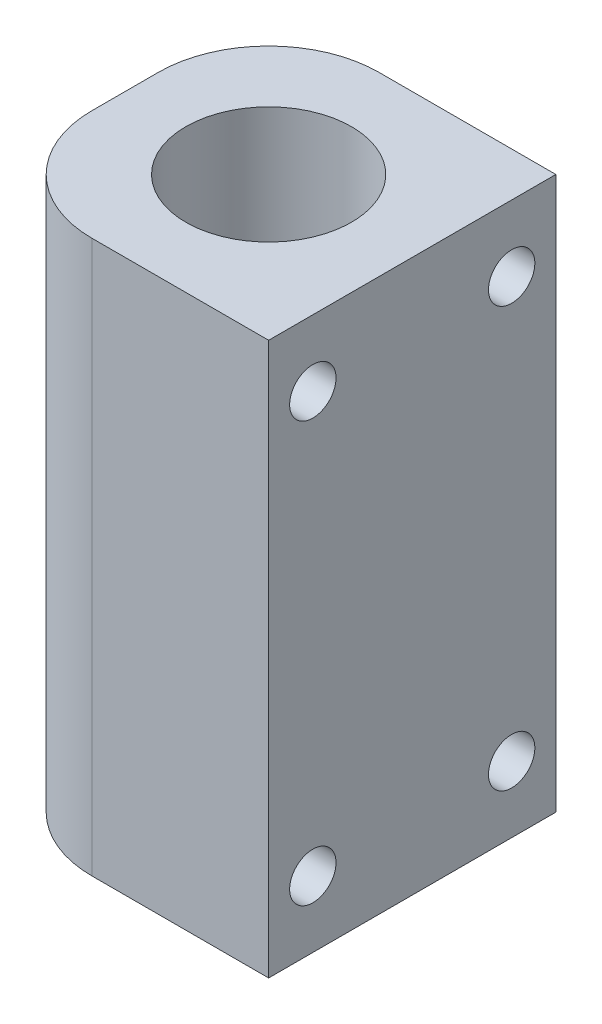
SolidWorks part; units mm, degrees
material "Alu - pink eloxiert"
ref_plane "Ebene vorne" through (0, 0, 0) normal (0, 0, 1) x (1, 0, 0)
ref_plane "Ebene oben" through (0, 0, 0) normal (0, 1, 0) x (1, 0, 0)
ref_plane "Ebene rechts" through (0, 0, 0) normal (1, 0, 0) x (0, 0, -1)
sketch "Skizze1" plane through (0, 0, 0) normal (0, 0, 1) x (1, 0, 0)
  line L1 (13, -25) -> (-13, -25)
  line L2 (13, -25) -> (13, 25)
  line L3 (13, 25) -> (-13, 25)
  line L4 (-13, -25) -> (-13, 25)
  line L5 (13, -25) -> (-13, 25) construction
  line L6 (13, 25) -> (-13, -25) construction
  point P0 (0, 0)
  dimension "D1" = 26
  dimension "D2" = 50
extrude "Aufsatz-Linear austragen1" add sketch "Skizze1" along normal blind 26
fillet "Verrundung1" radius 10 2 edges at (-13, 0, 0) (-13, 0, 26)
sketch "Skizze2" plane through (0, 25, 0) normal (0, 1, 0) x (1, 0, 0)
  line L0 (13, 0) -> (-3, 0) construction
  line L1 (-13, -16) -> (-13, -10) construction
  circle A0 centre (0, -13) radius 7.5
  dimension "D1" = 15
  dimension "D2" = 13
  dimension "D3" = 13
extrude "Schnitt-Linear austragen1" cut sketch "Skizze2" against normal through all
hole_wizard "M5 Gewindebohrung1" positions "Skizze3" profile "Skizze4" tap size "M5" standard "DIN"
sketch "Skizze3" plane through (13, 0, 0) normal (1, 0, 0) x (0, 0, -1)
  line L0 (-26, -25) -> (0, -25) construction
  point P0 (-22, 19)
  point P2 (-4, 19)
  point P4 (-22, -19)
  point P6 (-4, -19)
  point P9 (0, 0)
  point P10 (0, 0)
  point P11 (0, 0)
  point P12 (0, 0)
  point P15 (-13, -25)
  dimension "D1" = 38
  dimension "D2" = 6
  dimension "D3" = 18
  dimension "D4" = 9
sketch "Skizze4" plane through (13, 19, 22) normal (0, 1, 0) x (0, 0, -1)
  line L0 (0, 0) -> (0, 10.2618)
  line L1 (0, 10.2618) -> (2.1, 9)
  line L2 (2.1, 9) -> (2.1, 0)
  line L5 (2.1, 0) -> (0, 0)
  line L10 (0, 10.2618) -> (-2.1, 9) construction
  line L11 (0, -6.35) -> (0, 107.95) construction
  dimension "Bohrerdurchmesser" = 4.2
  dimension "Bohrungstiefe" = 9
  dimension "Spitzenwinkel" = 118
cosmetic thread "Bohrungsgewinde1" parameters "D1"=7, "D2"=5
cosmetic thread "Bohrungsgewinde2" parameters "D1"=7, "D2"=5
cosmetic thread "Bohrungsgewinde3" parameters "D1"=7, "D2"=5
cosmetic thread "Bohrungsgewinde4" parameters "D1"=7, "D2"=5
